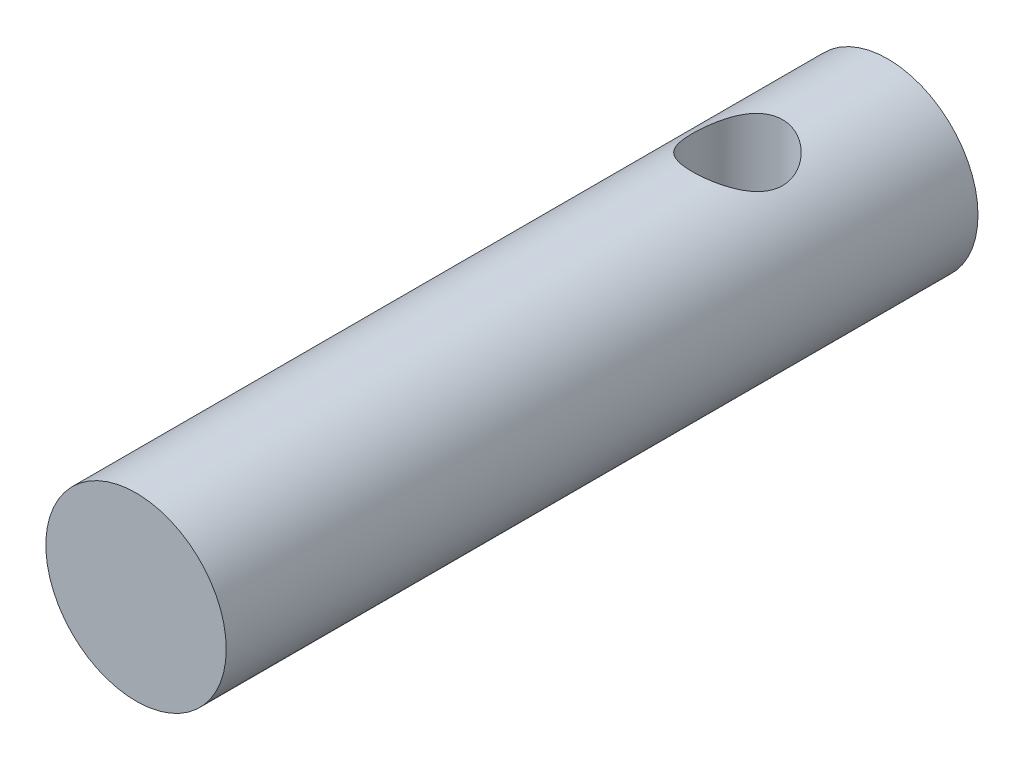
SolidWorks part; units mm, degrees
material "6061 Alloy"
ref_plane "Front Plane" through (0, 0, 0) normal (0, 0, 1) x (1, 0, 0)
ref_plane "Top Plane" through (0, 0, 0) normal (0, 1, 0) x (1, 0, 0)
ref_plane "Right Plane" through (0, 0, 0) normal (1, 0, 0) x (0, 0, -1)
sketch "Sketch1" plane through (0, 0, 0) normal (0, 0, 1) x (1, 0, 0)
  circle A0 centre (0, 0) radius 3
  dimension "D1" = 6
extrude "Boss-Extrude1" add sketch "Sketch1" along normal blind 25
sketch "Sketch2" plane through (0, 0, 0) normal (0, 1, 0) x (1, 0, 0)
  line L0 (3, 0) -> (-3, 0) construction
  circle A0 centre (0, -5) radius 1.5
  dimension "D1" = 3
  dimension "D2" = 5
extrude "Cut-Extrude1" cut sketch "Sketch2" against normal through all both and the other way through all
